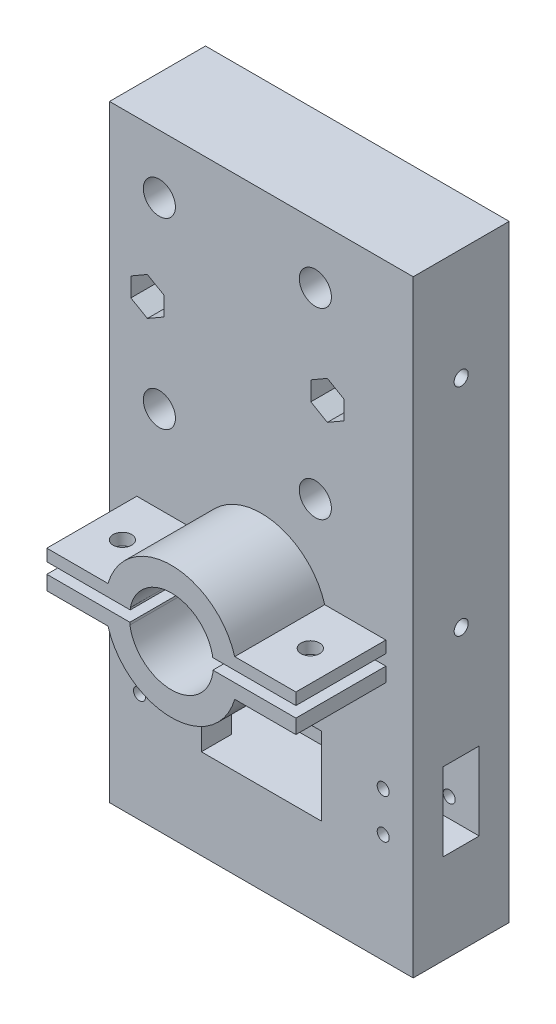
SolidWorks part; units mm, degrees
other "Markup1"
sketch "Sketch8" plane through (21.3115, 25, 0) normal (0.306, 0.1864, -0.9336) x (-0.9512, 0.0181, -0.3081)
ref_plane "Front Plane" through (0, 0, 0) normal (0, 0, 1) x (1, 0, 0)
ref_plane "Top Plane" through (0, 0, 0) normal (0, 1, 0) x (1, 0, 0)
ref_plane "Right Plane" through (0, 0, 0) normal (1, 0, 0) x (0, 0, -1)
sketch "Sketch1" plane through (0, 0, 0) normal (0, 0, 1) x (1, 0, 0)
  line L0 (0, 25) -> (0, -25) construction
  line L1 (21.3115, 25) -> (-21.3115, 25)
  line L2 (21.3115, 25) -> (21.3115, -25)
  line L3 (21.3115, -25) -> (-21.3115, -25)
  line L4 (-21.3115, 25) -> (-21.3115, -25)
  line L5 (21.3115, 25) -> (-21.3115, -25) construction
  line L6 (21.3115, -25) -> (-21.3115, 25) construction
  line L7 (-21.3115, 0) -> (21.3115, 0) construction
  circle A0 centre (-13, -15.25) radius 2.677
  circle A1 centre (13, -15.25) radius 2.677
  circle A2 centre (13, 15.25) radius 2.677
  circle A3 centre (-13, 15.25) radius 2.677
  point P0 (0, 0)
  dimension "D1" = 30.5
  dimension "D2" = 26
  dimension "D3" = 50
extrude "Boss-Extrude1" add sketch "Sketch1" along normal blind 16
sketch "Sketch2" plane through (0, 0, 0) normal (0, 0, 1) x (1, 0, 0)
  circle A0 centre (0, 0) radius 11.04
  dimension "D1" = 22.08
extrude "Cut-Extrude2" cut sketch "Sketch2" along normal blind 11
sketch "Sketch3" plane through (0, 0, 0) normal (0, 0, -1) x (-1, 0, 0)
  line L0 (0, 0) -> (-18.0234, 0) construction
  line L1 (0, 0) -> (0, 5.0894) construction
  circle A0 centre (-15, 0) radius 1.75
  circle A1 centre (15, 0) radius 1.75
  dimension "D1" = 15
  dimension "D2" = 3.5
extrude "Cut-Extrude3" cut sketch "Sketch3" against normal blind 10
sketch "Sketch9" plane through (0, 0, 0) normal (0, 0, -1) x (-1, 0, 0)
  line L0 (0, -11.04) -> (0, 11.04) construction
  line L1 (-15, 3.1754) -> (-17.75, 1.5877)
  line L2 (-17.75, 1.5877) -> (-17.75, -1.5877)
  line L3 (-17.75, -1.5877) -> (-15, -3.1754)
  line L4 (-15, -3.1754) -> (-12.25, -1.5877)
  line L5 (-12.25, -1.5877) -> (-12.25, 1.5877)
  line L6 (-12.25, 1.5877) -> (-15, 3.1754)
  line L7 (12.25, 1.5877) -> (15, 3.1754)
  line L8 (12.25, -1.5877) -> (12.25, 1.5877)
  line L9 (15, -3.1754) -> (12.25, -1.5877)
  line L10 (17.75, -1.5877) -> (15, -3.1754)
  line L11 (17.75, 1.5877) -> (17.75, -1.5877)
  line L12 (15, 3.1754) -> (17.75, 1.5877)
  circle A0 centre (-15, 0) radius 2.75 construction
  circle A1 centre (0, 0) radius 11.04 construction
  point P1 (-17.75, 0)
  dimension "D1" = 5.5
extrude "Cut-Extrude6" cut sketch "Sketch9" against normal through all from offset 5 offset against normal yes
sketch "Sketch30" plane through (0, -25, 0) normal (0, -1, 0) x (1, 0, 0)
  line L1 (-21.3115, 16) -> (21.3115, 16)
  line L2 (-21.3115, 16) -> (-21.3115, 0)
  line L3 (-21.3115, 0) -> (21.3115, 0)
  line L4 (21.3115, 16) -> (21.3115, 0)
extrude "Boss-Extrude8" add sketch "Sketch30" along normal blind 20.23
sketch "Sketch10" plane through (0, 0, 0) normal (0, 0, 1) x (1, 0, 0)
  line L0 (21.3115, -45.23) -> (-21.3115, -45.23)
  line L2 (-21.3115, -45.23) -> (-21.3115, -61.23)
  line L3 (-21.3115, -61.23) -> (21.3115, -61.23)
  line L4 (21.3115, -61.23) -> (21.3115, -45.23)
  dimension "D1" = 16
extrude "Boss-Extrude2" add sketch "Sketch10" along normal up to surface (16 mm away) up to face at (15, 0, 16)
sketch "Sketch14" plane through (-21.3115, 0, 0) normal (-1, 0, 0) x (0, 0, 1)
  line L0 (16, -61.23) -> (0, -61.23) construction
  line L1 (5, -61.23) -> (11, -61.23)
  line L2 (5, -61.23) -> (5, -48.23)
  line L3 (5, -48.23) -> (11, -48.23)
  line L4 (11, -61.23) -> (11, -48.23)
  line L7 (0, -61.23) -> (16, -61.23) construction
  point P6 (8, -61.23)
  point P7 (8, -61.23)
  dimension "D1" = 13
  dimension "D2" = 6
extrude "Cut-Extrude7" cut sketch "Sketch14" against normal through all
sketch "Sketch16" plane through (21.3115, 0, 0) normal (1, 0, 0) x (0, 0, -1)
  line L0 (-8, -48.23) -> (-8, 25)
  line L1 (-11, -48.23) -> (-5, -48.23) construction
  line L2 (-16, 25) -> (0, 25) construction
  line L4 (-16, 25) -> (0, 25)
  line L5 (-16, 25) -> (-16, -48.23)
  line L6 (-16, -48.23) -> (0, -48.23)
  line L7 (0, 25) -> (0, -48.23)
  line M6 (-11, -48.23) -> (-5, -48.23)
  line M9 (0, -61.23) -> (0, 25)
  line M10 (0, 25) -> (-16, 25)
  line M11 (-16, 25) -> (-16, -61.23)
extrude "Boss-Extrude3" add sketch "Sketch16" along normal blind 8 contours L6 L0 M11 M6 M10 | L6 L0 M6 M9 M10
sketch "Sketch17" plane through (29.3115, 0, 0) normal (1, 0, 0) x (0, 0, -1)
  line L0 (-8, -48.23) -> (-8, 25)
  line L1 (-16, -48.23) -> (0, -48.23) construction
  line L2 (0, 25) -> (-16, 25) construction
  line L3 (-8, -11.615) -> (0, -11.615)
  line L4 (0, -48.23) -> (0, 25) construction
  circle A0 centre (-8, 6.385) radius 1.175
  circle A1 centre (-8, -29.615) radius 1.175
  point P8 (-8, -11.615)
  dimension "D2" = 2.35
  dimension "D1" = 18
extrude "Cut-Extrude9" cut sketch "Sketch17" against normal blind 8 contours L0 A0 | L0 A0 | A1 L0 | A1 L0
sketch "Sketch18" plane through (0, 0, 0) normal (0, 0, -1) x (-1, 0, 0)
  line L0 (-25.3115, -48.23) -> (-25.3115, 25)
  line L1 (-29.3115, -48.23) -> (-21.3115, -48.23) construction
  line L2 (-29.3115, 25) -> (21.3115, 25) construction
  line L3 (-25.3115, -11.615) -> (-29.3115, -11.615)
  line L4 (-26.2115, 8.385) -> (-24.4115, 8.385)
  line L5 (-26.2115, 8.385) -> (-26.2115, 4.385)
  line L6 (-26.2115, 4.385) -> (-24.4115, 4.385)
  line L7 (-24.4115, 8.385) -> (-24.4115, 4.385)
  line L8 (-26.2115, 8.385) -> (-24.4115, 4.385) construction
  line L9 (-26.2115, 4.385) -> (-24.4115, 8.385) construction
  line L10 (-29.3115, -48.23) -> (-29.3115, 25) construction
  line L11 (-26.2115, -27.615) -> (-24.4115, -27.615)
  line L12 (-24.4115, -31.615) -> (-24.4115, -27.615)
  line L13 (-26.2115, -31.615) -> (-24.4115, -31.615)
  line L14 (-26.2115, -31.615) -> (-26.2115, -27.615)
  point P6 (-25.3115, 6.385)
  point P11 (-25.3115, -11.615)
  dimension "D1" = 18
  dimension "D2" = 4
  dimension "D3" = 1.8
extrude "Cut-Extrude10" cut sketch "Sketch18" against normal blind 10.2 contours L7 L4 L0 L6 | L5 L6 L0 L4 | L14 L11 L12 L13
sketch "Sketch15" plane through (0, 0, 0) normal (0, 0, -1) x (-1, 0, 0)
  line L0 (21.3115, -61.23) -> (-21.3115, -61.23) construction
  line L1 (-29.3115, -23.2996) -> (21.3115, -23.2996)
  line L2 (-21.3115, -61.23) -> (-21.3115, -48.23)
  line L3 (-29.3115, -48.23) -> (-29.3115, 25) construction
  line L4 (-4, -23.2996) -> (-4, -61.23)
  line L7 (-21.3115, -61.23) -> (-21.3115, -48.23) construction
  line L8 (-21.3115, -48.23) -> (-21.3115, -61.23) construction
  line L9 (-21.3115, -54.73) -> (21.3115, -54.73)
  line L10 (21.3115, 25) -> (21.3115, -61.23) construction
  line L11 (21.3115, -54.73) -> (21.3115, -28)
  line L12 (21.3115, -28) -> (0, -28)
  line L13 (0, -28) -> (0, -61.23)
  circle A2 centre (16.3115, -58.03) radius 1
  circle A4 centre (16.3115, -51.43) radius 1
  point P11 (-21.3115, -61.23)
  dimension "D1" = 5
  dimension "D2" = 3.2
extrude "Cut-Extrude8" cut sketch "Sketch15" against normal through all and the other way through all
sketch "Sketch6" plane through (0, -48.23, 0) normal (0, -1, 0) x (1, 0, 0)
  line L0 (21.3115, 11) -> (-21.3115, 11) construction
  line L1 (4.517, 11) -> (-4.517, 11)
  line L2 (4.517, 11) -> (4.517, 14.85)
  line L3 (4.517, 14.85) -> (-4.517, 14.85)
  line L4 (-4.517, 11) -> (-4.517, 14.85)
  line L5 (4.517, 11) -> (-4.517, 14.85) construction
  line L6 (4.517, 14.85) -> (-4.517, 11) construction
  point P0 (0, 12.925)
  dimension "D1" = 3.85
extrude "Cut-Extrude5" cut sketch "Sketch6" against normal blind 50 and the other way through all
sketch "Sketch20" plane through (0, -48.23, 0) normal (0, -1, 0) x (-1, 0, 0)
  line L1 (-21.3115, -16) -> (-29.3115, -16)
  line L2 (-21.3115, -16) -> (-21.3115, 0)
  line L3 (-21.3115, 0) -> (-29.3115, 0)
  line L4 (-29.3115, -16) -> (-29.3115, 0)
extrude "Boss-Extrude5" add sketch "Sketch20" along normal up to surface (13 mm away) up to face at (0, -61.23, 13.2125)
sketch "Sketch21" plane through (0, -61.23, 0) normal (0, -1, 0) x (-1, 0, 0)
  line L0 (-29.3115, -16) -> (-29.3115, 0) construction
  line L1 (-21.3115, -11) -> (-29.3115, -11)
  line L2 (-21.3115, -11) -> (-21.3115, -5)
  line L3 (-21.3115, -5) -> (-29.3115, -5)
  line L4 (-29.3115, -11) -> (-29.3115, -5)
extrude "Cut-Extrude11" cut sketch "Sketch21" against normal up to surface (13 mm away) up to face at (0, -48.23, 9)
sketch "Sketch22" plane through (0, 0, 0) normal (0, 0, -1) x (-1, 0, 0)
  line L0 (21.3115, -61.23) -> (-29.3115, -61.23) construction
  line L1 (-29.3115, -61.23) -> (-29.3115, 25) construction
  circle A0 centre (-24.3115, -58.03) radius 1
  circle A3 centre (-24.3115, -51.43) radius 1
  dimension "D1" = 2
  dimension "D2" = 3.2
  dimension "D3" = 5
  dimension "D4" = 6.6
  dimension "D5" = 2
  dimension "D6" = 5
extrude "Cut-Extrude12" cut sketch "Sketch22" against normal through all
sketch "Sketch24" plane through (0, -61.23, 0) normal (0, -1, 0) x (1, 0, 0)
  line L1 (-21.3115, 5) -> (29.3115, 5)
  line L2 (-21.3115, 5) -> (-21.3115, 0)
  line L3 (-21.3115, 0) -> (29.3115, 0)
  line L4 (29.3115, 5) -> (29.3115, 0)
extrude "Boss-Extrude6" add sketch "Sketch24" along normal blind 15
sketch "Sketch25" plane through (0, 0, 5) normal (0, 0, 1) x (1, 0, 0)
  line L0 (29.3115, -76.23) -> (-21.3115, -76.23) construction
  line L1 (-21.3115, -76.23) -> (29.3115, -76.23)
  line L2 (-21.3115, -76.23) -> (-21.3115, -61.23)
  line L3 (-21.3115, -61.23) -> (29.3115, -61.23)
  line L4 (29.3115, -76.23) -> (29.3115, -61.23)
extrude "Boss-Extrude7" add sketch "Sketch25" along normal up to surface (11 mm away) up to face at (23.3115, -58.03, 16)
sketch "Sketch26" plane through (0, -76.23, 0) normal (0, -1, 0) x (1, 0, 0)
  line L0 (4, 16) -> (4, 0)
  line L1 (29.3115, 16) -> (-21.3115, 16) construction
  line L2 (-21.3115, 0) -> (29.3115, 0) construction
  line L3 (4, 8) -> (-21.3115, 8)
  line L4 (-21.3115, 16) -> (-21.3115, 0) construction
  circle A0 centre (-14, 8) radius 1
  circle A1 centre (22, 8) radius 1
  dimension "D1" = 2
  dimension "D2" = 18
extrude "Cut-Extrude13" cut sketch "Sketch26" against normal blind 10 contours L3 A0 | L3 A0 | A1
sketch "Sketch27" plane through (0, 0, 0) normal (0, 0, -1) x (-1, 0, 0)
  line L0 (-24.4115, -31.615) -> (-24.4115, -27.615) construction
  line L1 (-24.0015, -71.33) -> (-20.0015, -71.33)
  line L2 (-24.0015, -71.33) -> (-24.0015, -73.13)
  line L3 (-24.0015, -73.13) -> (-20.0015, -73.13)
  line L4 (-20.0015, -71.33) -> (-20.0015, -73.13)
  line L5 (-24.0015, -71.33) -> (-20.0015, -73.13) construction
  line L6 (-24.0015, -73.13) -> (-20.0015, -71.33) construction
  line L8 (-26.2115, -31.615) -> (-24.4115, -31.615) construction
  line L12 (-29.3115, -76.23) -> (-29.3115, 25) construction
  line L13 (21.3115, -76.23) -> (-29.3115, -76.23) construction
  line L14 (-29.3115, -49.5626) -> (21.3115, -49.5626)
  line L15 (21.3115, 25) -> (21.3115, -76.23) construction
  line L16 (-4, -49.5626) -> (-4, -76.23)
  line L17 (16.0015, -73.13) -> (12.0015, -73.13)
  line L18 (12.0015, -71.33) -> (12.0015, -73.13)
  line L19 (16.0015, -71.33) -> (12.0015, -71.33)
  line L20 (16.0015, -71.33) -> (16.0015, -73.13)
  point P0 (-22.0015, -72.23)
  dimension "D1" = 7.31
  dimension "D2" = 3.1
extrude "Cut-Extrude14" cut sketch "Sketch27" against normal blind 10.2 contours L4 L1 L2 L3 | L20 L19 L18 L17
sketch "Sketch29" plane through (0, 0, 16) normal (0, 0, 1) x (1, 0, 0)
  line L0 (-16.3115, -51.43) -> (24.3115, -58.03)
  line L1 (24.3115, -51.43) -> (-16.3115, -58.03)
  line L2 (-16.3115, -51.43) -> (24.3115, -51.43)
  line L3 (-16.3115, -51.43) -> (-16.3115, -58.03)
  line L4 (-16.3115, -58.03) -> (24.3115, -58.03)
  line L5 (24.3115, -51.43) -> (24.3115, -58.03)
  line L7 (-6, -48.23) -> (14, -48.23)
  line L8 (-6, -48.23) -> (-6, -61.23)
  line L9 (-6, -61.23) -> (14, -61.23)
  line L10 (14, -48.23) -> (14, -61.23)
  line L11 (-6, -48.23) -> (14, -61.23) construction
  line L12 (-6, -61.23) -> (14, -48.23) construction
  circle A0 centre (-16.3115, -51.43) radius 1 construction
  point P4 (4, -54.73)
  dimension "D1" = 13
  dimension "D2" = 20
extrude "Cut-Extrude15" cut sketch "Sketch29" against normal up to surface (5 mm away) contours L10 L7 L8 L2 | L10 L2 L8 L0 L1 | L0 L8 L1 | L10 L4 L8 L9 | L10 L0 L1 L8 L4 | L10 L1 L0 up to face at (-16.3115, -59.03, 11)
sketch "Sketch31" plane through (0, 0, 0) normal (0, 0, -1) x (-1, 0, 0)
  line L5 (-4.5, 14.04) -> (4.5, 14.04)
  line L6 (-4.5, 14.04) -> (-4.5, 8.04)
  line L7 (-4.5, -8.04) -> (4.5, -8.04)
  line L8 (-4.5, -8.04) -> (-4.5, -14.04)
  line L9 (-4.5, -14.04) -> (4.5, -14.04)
  line L10 (4.5, -8.04) -> (4.5, -14.04)
  line L11 (-4.5, -8.04) -> (4.5, -14.04) construction
  line L12 (-4.5, -14.04) -> (4.5, -8.04) construction
  line L13 (-4.5, 8.04) -> (4.5, 8.04)
  line L14 (4.5, 14.04) -> (4.5, 8.04)
  line L15 (-4.5, 14.04) -> (4.5, 8.04) construction
  line L16 (-4.5, 8.04) -> (4.5, 14.04) construction
  circle A1 centre (0, 0) radius 11.04 construction
  point P0 (-11.04, 0)
  point P1 (0, 11.04)
  point P8 (0, -11.04)
  dimension "D1" = 6
  dimension "D2" = 9
  dimension "D3" = 9
  dimension "D4" = 6
extrude "Cut-Extrude16" cut sketch "Sketch31" against normal up to surface (11 mm away) up to face at (0, 1.1266, 11)
sketch "Sketch32" plane through (0, 0, 16) normal (0, 0, 1) x (1, 0, 0)
  line L2 (-21.3115, 25) -> (-21.3115, -76.23) construction
  line L24 (14.5594, -29.7152) -> (24.7586, -29.7152)
  line L25 (-14.3528, -31.6808) -> (-2.8528, -31.6808)
  line L27 (-14.3528, -33.4838) -> (-2.9147, -33.4838)
  line L29 (-2.8528, -31.3568) -> (-2.8528, -31.6808)
  line L30 (-2.9147, -33.8911) -> (-2.9147, -33.4838)
  line L31 (10.9117, -33.8911) -> (10.9117, -33.4838)
  line L32 (10.8592, -31.6808) -> (10.8498, -31.3568)
  line L33 (10.8592, -31.6808) -> (22.3498, -31.6808)
  line L34 (10.9117, -33.4838) -> (22.3498, -33.4838)
  line L35 (-16.7615, -29.7152) -> (-6.5624, -29.7152)
  line L36 (-16.7615, -29.7152) -> (-16.7615, -31.6808)
  line L37 (-16.7615, -35.8689) -> (-6.5624, -35.8689)
  line L38 (24.7586, -29.7152) -> (24.7586, -31.6808)
  line L39 (14.5594, -35.8689) -> (24.7586, -35.8689)
  line L40 (-14.3528, -31.6808) -> (-16.7615, -31.6808)
  line L41 (-14.3528, -33.4838) -> (-16.7615, -33.4838)
  line L42 (22.3498, -31.6808) -> (24.7586, -31.6808)
  line L43 (22.3498, -33.4838) -> (24.7586, -33.4838)
  line L44 (-16.7615, -33.4838) -> (-16.7615, -35.8689)
  line L45 (24.7586, -33.4838) -> (24.7586, -35.8689)
  arc A0 (-2.9147, -33.8911) -> (10.9117, -33.8911) centre (3.9985, -32.792) ccw
  arc A1 (-6.5624, -35.8689) -> (14.5594, -35.8689) centre (3.9985, -32.792) ccw
  arc A2 (14.5594, -29.7152) -> (-6.5624, -29.7152) centre (3.9985, -32.792) ccw
  arc A3 (10.8498, -31.3568) -> (-2.8528, -31.3568) centre (3.9985, -32.792) ccw
  dimension "D1" = 25.31
extrude "Boss-Extrude9" add sketch "Sketch32" along normal blind 15
sketch "Sketch35" plane through (0, 0, 16) normal (0, 0, 1) x (1, 0, 0)
  circle A0 centre (3.9985, -32.792) radius 7
extrude "Cut-Extrude17" cut sketch "Sketch35" against normal through all
sketch "Sketch46" plane through (0, -76.23, 0) normal (0, -1, 0) x (1, 0, 0)
  line L0 (29.3115, 16) -> (-21.3115, 16) construction
  line L2 (-16.7615, 31) -> (-16.7615, 16) construction
  line L3 (24.7586, 31) -> (24.7586, 16) construction
  circle A0 centre (-11.6615, 23.5) radius 1.55
  circle A1 centre (19.6586, 23.5) radius 1.55
  dimension "D1" = 7.5
  dimension "D3" = 5.1
  dimension "D2" = 5.1
extrude "Cut-Extrude29" cut sketch "Sketch46" against normal through all
